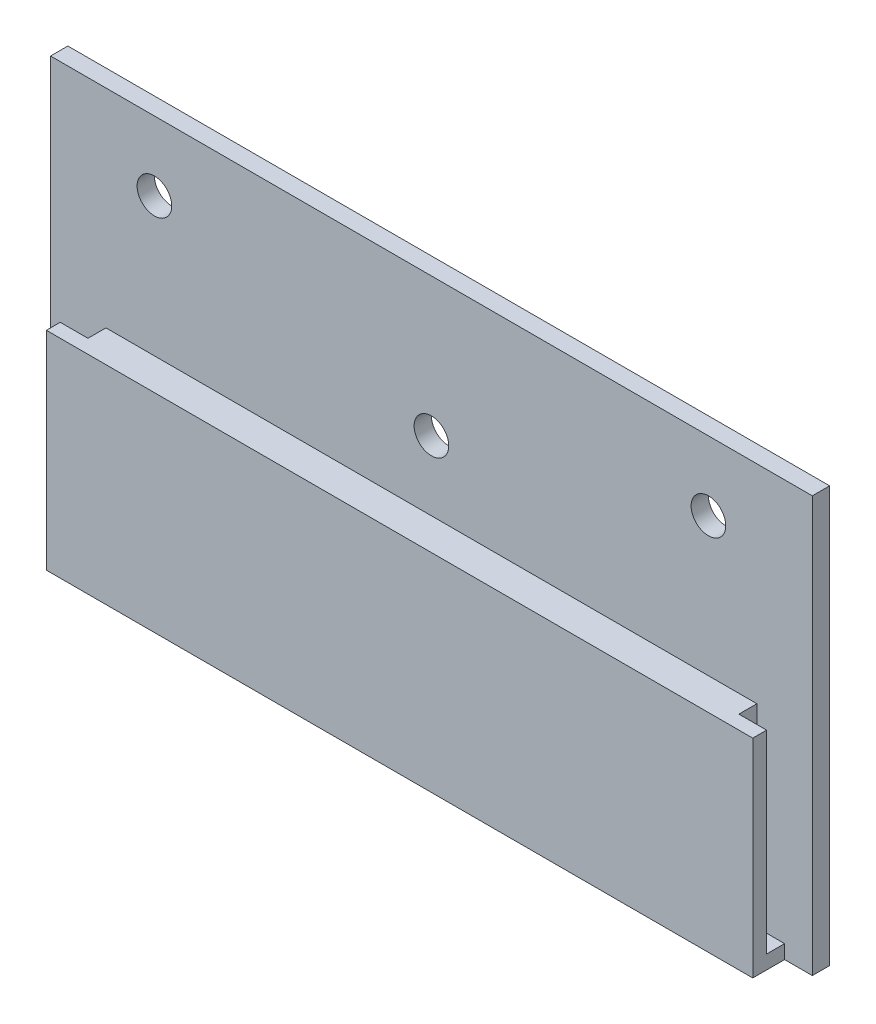
SolidWorks part; units mm, degrees
ref_plane "Front Plane" through (0, 0, 0) normal (0, 0, 1) x (1, 0, 0)
ref_plane "Top Plane" through (0, 0, 0) normal (0, 1, 0) x (1, 0, 0)
ref_plane "Right Plane" through (0, 0, 0) normal (1, 0, 0) x (0, 0, -1)
sketch "Sketch3" plane through (0, 0, 0) normal (0, 0, 1) x (1, 0, 0)
  line L1 (0, 0) -> (139.7, 0)
  line L2 (0, 0) -> (0, -76.2)
  line L3 (0, -76.2) -> (139.7, -76.2)
  line L4 (139.7, 0) -> (139.7, -76.2)
  dimension "D1" = 76.2
  dimension "D2" = 139.7
extrude "Boss-Extrude1" add sketch "Sketch3" along normal blind 3.175 contours L2 L3 L4 L1
sketch "Sketch4" plane through (0, 0, 3.175) normal (0, 0, 1) x (1, 0, 0)
  line L0 (0, -76.2) -> (139.7, -76.2) construction
  line L1 (10.16, -76.2) -> (129.54, -76.2)
  line L2 (10.16, -76.2) -> (10.16, -38.1)
  line L3 (10.16, -38.1) -> (129.54, -38.1)
  line L4 (129.54, -76.2) -> (129.54, -38.1)
  line L5 (0, 0) -> (139.7, 0) construction
  point P8 (69.85, 0)
  point P9 (69.85, -38.1)
  dimension "D1" = 119.38
  dimension "D2" = 38.1
extrude "Boss-Extrude2" add sketch "Sketch4" along normal blind 3.302
sketch "Sketch6" plane through (0, 0, 6.477) normal (0, 0, 1) x (1, 0, 0)
  line L0 (129.54, -76.2) -> (139.7, -76.2) construction
  line L1 (5.08, -38.1) -> (134.62, -38.1)
  line L2 (5.08, -38.1) -> (5.08, -76.2)
  line L3 (5.08, -76.2) -> (134.62, -76.2)
  line L4 (134.62, -38.1) -> (134.62, -76.2)
  line L5 (10.16, -38.1) -> (10.16, -76.2) construction
  dimension "D1" = 5.08
  dimension "D2" = 38.1
extrude "Boss-Extrude3" add sketch "Sketch6" along normal blind 2.54
sketch "Sketch7" plane through (0, -76.2, 0) normal (0, -1, 0) x (1, 0, 0)
  line L0 (0, 0) -> (139.7, 0) construction
  line L1 (5.08, 9.017) -> (134.62, 9.017)
  line L2 (5.08, 9.017) -> (5.08, 0)
  line L3 (5.08, 0) -> (134.62, 0)
  line L4 (134.62, 9.017) -> (134.62, 0)
  line L5 (134.62, 9.017) -> (134.62, 6.477) construction
extrude "Boss-Extrude4" add sketch "Sketch7" against normal blind 2.54
sketch "Sketch8" plane through (0, 0, 3.175) normal (0, 0, 1) x (1, 0, 0)
  line L0 (19.05, -12.7) -> (120.65, -12.7) construction
  line L1 (0, 0) -> (139.7, 0) construction
  circle A0 centre (19.05, -12.7) radius 3.175
  circle A1 centre (69.85, -25.4) radius 3.175
  circle A2 centre (120.65, -12.7) radius 3.175
  point P6 (69.85, -12.7)
  point P9 (69.85, 0)
  dimension "D1" = 6.35
  dimension "D2" = 12.7
  dimension "D3" = 12.7
  dimension "D4" = 50.8
extrude "Cut-Extrude1" cut sketch "Sketch8" against normal through all both and the other way through all
